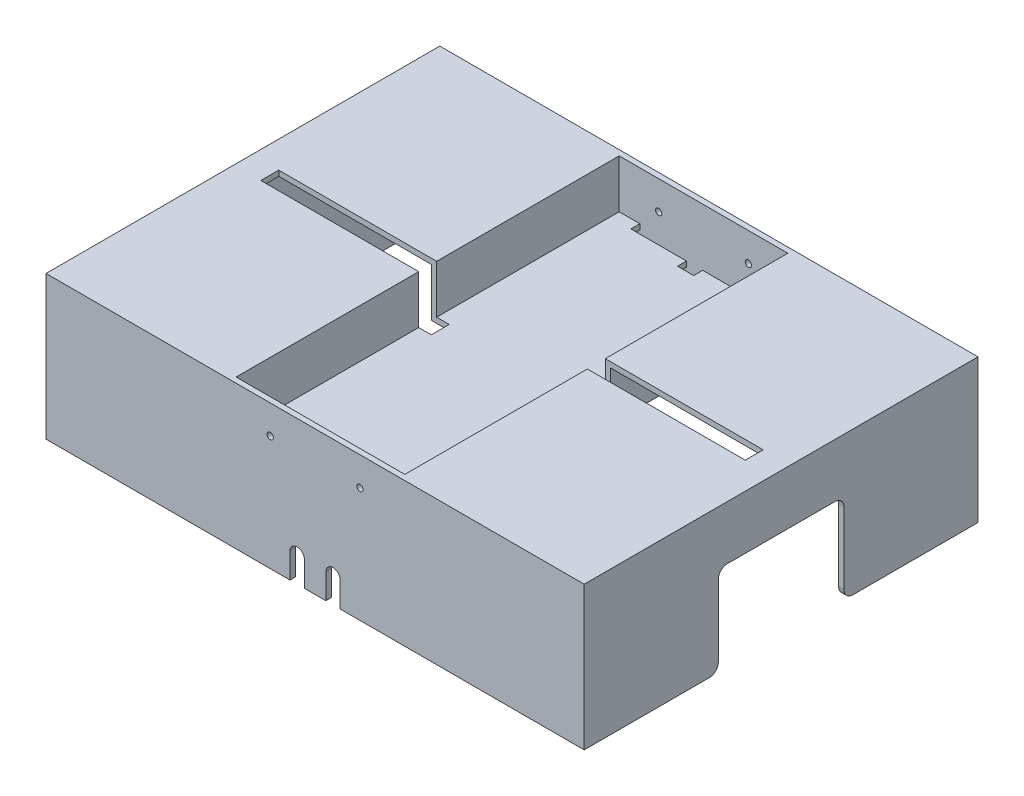
SolidWorks part; units mm, degrees
ref_plane "Front Plane" through (0, 0, 0) normal (0, 0, 1) x (1, 0, 0)
ref_plane "Top Plane" through (0, 0, 0) normal (0, 1, 0) x (1, 0, 0)
ref_plane "Right Plane" through (0, 0, 0) normal (1, 0, 0) x (0, 0, -1)
sketch "Sketch1" plane through (0, 0, 0) normal (0, 1, 0) x (1, 0, 0)
  line L1 (-150, 106.75) -> (-50, 106.75)
  line L2 (-150, 106.75) -> (-150, -106.75)
  line L3 (-150, -106.75) -> (-50, -106.75)
  line L4 (-50, 106.75) -> (-50, -106.75)
  line L5 (-150, 106.75) -> (-50, -106.75) construction
  line L6 (-150, -106.75) -> (-50, 106.75) construction
  line L7 (50, 106.75) -> (150, 106.75)
  line L8 (50, 106.75) -> (50, -106.75)
  line L9 (50, -106.75) -> (150, -106.75)
  line L10 (150, 106.75) -> (150, -106.75)
  line L11 (50, 106.75) -> (150, -106.75) construction
  line L12 (50, -106.75) -> (150, 106.75) construction
  point P0 (-100, 0)
  point P5 (100, 0)
  dimension "D1" = 213.5
  dimension "D2" = 100
  dimension "D3" = 50
  dimension "D4" = 50
extrude "Boss-Extrude1" add sketch "Sketch1" along normal blind 3
sketch "Sketch2" plane through (0, 0, 106.75) normal (0, 0, 1) x (1, 0, 0)
  line L1 (-150, 3) -> (150, 3)
  line L2 (-150, 3) -> (-150, -77)
  line L3 (-150, -77) -> (150, -77)
  line L4 (150, 3) -> (150, -77)
  dimension "D1" = 80
extrude "Boss-Extrude2" add sketch "Sketch2" along normal blind 3
mirror "Mirror1" about plane through (0, 0, 0) normal (0, 0, 1) of "Boss-Extrude2"
sketch "Sketch4" plane through (0, 3, 0) normal (0, 1, 0) x (1, 0, 0)
  line L0 (50, -106.75) -> (-50, -106.75) construction
  line L5 (-50, 106.75) -> (-47, 106.75)
  line L6 (-50, 106.75) -> (-50, -106.75)
  line L7 (-50, -106.75) -> (-47, -106.75)
  line L8 (-47, 106.75) -> (-47, -106.75)
  line L9 (50, 106.75) -> (-50, 106.75) construction
  line L10 (50, -106.75) -> (47, -106.75)
  line L11 (50, -106.75) -> (50, 106.75)
  line L12 (50, 106.75) -> (47, 106.75)
  line L13 (47, -106.75) -> (47, 106.75)
  dimension "D1" = 3
extrude "Boss-Extrude4" add sketch "Sketch4" against normal blind 30
sketch "Sketch5" plane through (0, -27, 0) normal (0, -1, 0) x (1, 0, 0)
  line L0 (-150, 106.75) -> (150, 106.75) construction
  line L1 (-47, -106.75) -> (47, -106.75)
  line L2 (-47, -106.75) -> (-47, 106.75)
  line L3 (-47, 106.75) -> (47, 106.75)
  line L4 (47, -106.75) -> (47, 106.75)
  line L5 (47, 106.75) -> (50, 106.75) construction
  line L6 (-150, -106.75) -> (150, -106.75) construction
extrude "Boss-Extrude5" add sketch "Sketch5" against normal blind 3
sketch "Sketch6" plane through (0, -24, 0) normal (0, 1, 0) x (1, 0, 0)
  line L0 (-35.5, 106.75) -> (35.5, 106.75)
  line L1 (35.5, 106.75) -> (35.5, 101.75)
  line L3 (35.5, 101.75) -> (4.5, 101.75)
  line L4 (4.5, 101.75) -> (4.5, 96.75)
  line L5 (4.5, 96.75) -> (-4.5, 96.75)
  line L6 (-4.5, 96.75) -> (-4.5, 101.75)
  line L7 (-4.5, 101.75) -> (-35.5, 101.75)
  line L9 (-35.5, 101.75) -> (-35.5, 106.75)
  line L10 (-35.5, -106.75) -> (35.5, -106.75)
  line L11 (35.5, -106.75) -> (35.5, -101.75)
  line L12 (35.5, -101.75) -> (4.5, -101.75)
  line L13 (4.5, -101.75) -> (4.5, -96.75)
  line L14 (4.5, -96.75) -> (-4.5, -96.75)
  line L15 (-4.5, -96.75) -> (-4.5, -101.75)
  line L16 (-4.5, -101.75) -> (-35.5, -101.75)
  line L17 (-35.5, -101.75) -> (-35.5, -106.75)
  line L18 (47, 106.75) -> (-47, 106.75) construction
  line L19 (-47, 106.75) -> (47, 106.75) construction
  line L20 (47, -106.75) -> (-47, -106.75) construction
  dimension "D1" = 5
  dimension "D2" = 9
  dimension "4.5" = 4.5
  dimension "D4" = 5
  dimension "D5" = 71
  dimension "D6" = 35.5
extrude "Cut-Extrude2" cut sketch "Sketch6" against normal up to next
sketch "Sketch3" plane through (0, 3, 0) normal (0, 1, 0) x (1, 0, 0)
  line L5 (-150, 109.75) -> (-150, -109.75) construction
  line L6 (-135, 5) -> (-40, 5)
  line L8 (-135, 5) -> (-135, -5)
  line L9 (-135, -5) -> (-40, -5)
  line L10 (-40, 5) -> (-40, -5)
  line L11 (-135, 5) -> (-40, -5) construction
  line L12 (-135, -5) -> (-40, 5) construction
  line L13 (40, 5) -> (135, 5)
  line L14 (40, 5) -> (40, -5)
  line L15 (40, -5) -> (135, -5)
  line L16 (135, 5) -> (135, -5)
  line L17 (40, 5) -> (135, -5) construction
  line L18 (40, -5) -> (135, 5) construction
  line L19 (150, -109.75) -> (150, 109.75) construction
  point P0 (-87.5, 0)
  point P6 (87.5, 0)
  dimension "D1" = 15
  dimension "D2" = 15
  dimension "D3" = 10
  dimension "D4" = 40
extrude "Cut-Extrude1" cut sketch "Sketch3" against normal up to next
sketch "Sketch7" plane through (-150, 0, 0) normal (-1, 0, 0) x (0, 0, 1)
  line L1 (-106.75, 0) -> (106.75, 0)
  line L2 (-106.75, 0) -> (-106.75, -77)
  line L3 (-106.75, -77) -> (106.75, -77)
  line L4 (106.75, 0) -> (106.75, -77)
extrude "Boss-Extrude6" add sketch "Sketch7" against normal blind 3
mirror "Mirror2" about plane through (0, 0, 0) normal (1, 0, 0) of "Boss-Extrude6"
sketch "Sketch8" plane through (0, 0, 109.75) normal (0, 0, 1) x (1, 0, 0)
  line L0 (-150, -77) -> (150, -77) construction
  line L1 (-14, -63) -> (-14, -77)
  line L2 (-14, -77) -> (-6, -77)
  line L3 (-6, -77) -> (-6, -63)
  line L4 (14, -63) -> (14, -77)
  line L5 (14, -77) -> (6, -77)
  line L6 (6, -77) -> (6, -63)
  circle A2 centre (-25, -13) radius 1.75
  circle A3 centre (25, -13) radius 1.75
  arc A4 (-14, -63) -> (-6, -63) centre (-10, -63) cw
  arc A5 (6, -63) -> (14, -63) centre (10, -63) cw
  dimension "D4" = 4
  dimension "D8" = 3.5
  dimension "D1" = 10
  dimension "D2" = 20
  dimension "D3" = 14
  dimension "D5" = 25
  dimension "D6" = 50
  dimension "D7" = 50
extrude "Cut-Extrude3" cut sketch "Sketch8" against normal through all
sketch "Sketch10" plane through (150, 0, 0) normal (1, 0, 0) x (0, 0, -1)
  line L0 (-109.75, -77) -> (109.75, -77) construction
  line L1 (-30, -27) -> (30, -27)
  line L2 (-35, -32) -> (-35, -77)
  line L3 (-35, -77) -> (35, -77)
  line L4 (35, -32) -> (35, -77)
  line L5 (-35, -27) -> (35, -77) construction
  line L6 (-35, -77) -> (35, -27) construction
  arc A1 (30, -27) -> (35, -32) centre (30, -32) cw
  arc A2 (-30, -27) -> (-35, -32) centre (-30, -32) ccw
  point P0 (0, -52)
  dimension "D3" = 5
  dimension "D1" = 50
  dimension "D2" = 70
extrude "Cut-Extrude4" cut sketch "Sketch10" against normal up to next
fillet "Fillet1" radius 5 2 edges at (148.5, -77, 35) (148.5, -77, -35)
